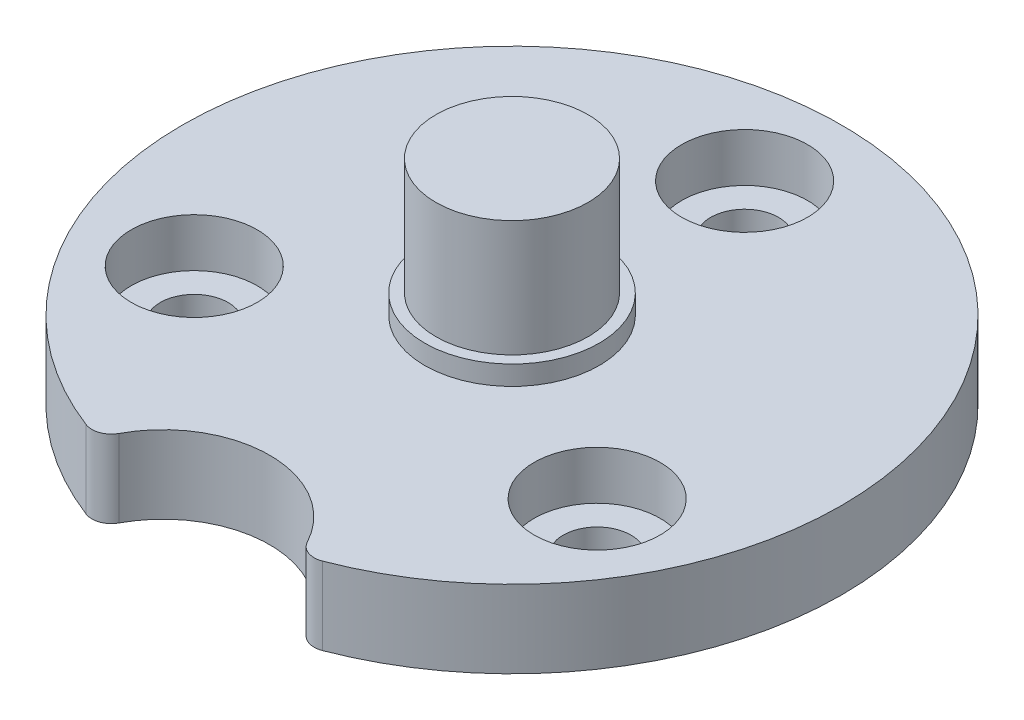
SolidWorks part; units mm, degrees
ref_plane "Front Plane" through (0, 0, 0) normal (0, 0, 1) x (1, 0, 0)
ref_plane "Top Plane" through (0, 0, 0) normal (0, 1, 0) x (1, 0, 0)
ref_plane "Right Plane" through (0, 0, 0) normal (1, 0, 0) x (0, 0, -1)
sketch "Sketch1" plane through (0, 0, 0) normal (0, 1, 0) x (1, 0, 0)
  line L0 (0, 0) -> (0, 15.6071) construction
  circle A0 centre (0, 0) radius 17
  circle A1 centre (0, 12) radius 1.75
  circle A2 centre (10.3923, -6) radius 1.75
  circle A3 centre (-10.3923, -6) radius 1.75
  point P12 (0, 0)
  dimension "D1" = 34
  dimension "D3" = 3.5
  dimension "D2" = 12
  dimension "D4" = 3
extrude "Boss-Extrude1" add sketch "Sketch1" along normal blind 4
sketch "Sketch2" plane through (0, 4, 0) normal (0, 1, 0) x (1, 0, 0)
  circle A0 centre (0, 12) radius 3.25
  circle A1 centre (10.3923, -6) radius 3.25
  circle A2 centre (-10.3923, -6) radius 3.25
  point P9 (0, 0)
  dimension "D1" = 6.5
  dimension "D2" = 3
extrude "Cut-Extrude1" cut sketch "Sketch2" against normal blind 2.5
sketch "Sketch3" plane through (0, 4, 0) normal (0, 1, 0) x (1, 0, 0)
  circle A0 centre (0, 0) radius 4.5
  dimension "D1" = 9
extrude "Boss-Extrude2" add sketch "Sketch3" along normal blind 1
sketch "Sketch4" plane through (0, 5, 0) normal (0, 1, 0) x (1, 0, 0)
  circle A0 centre (0, 0) radius 3.925
  dimension "D1" = 7.85
extrude "Boss-Extrude3" add sketch "Sketch4" along normal blind 6
sketch "Sketch5" plane through (0, 4, 0) normal (0, 1, 0) x (1, 0, 0)
  circle A0 centre (0, -18) radius 5.5
  point P2 (1.2159, -23.7399)
  point P5 (0, 0)
  dimension "D1" = 11
  dimension "D2" = 18
extrude "Cut-Extrude2" cut sketch "Sketch5" against normal up to next
fillet "Fillet1" radius 1 2 edges at (-5.1928, 2, 16.1875) (5.1928, 2, 16.1875)
